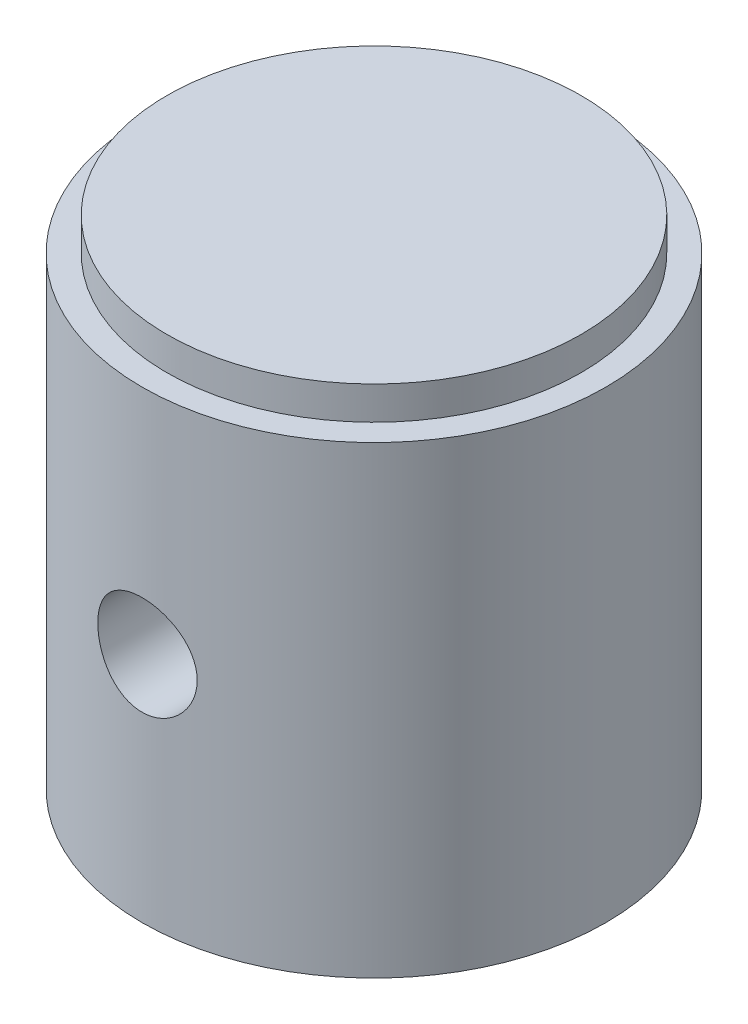
SolidWorks part; units mm, degrees
material "1023 Carbon Steel Sheet (SS)"
ref_plane "Front Plane" through (0, 0, 0) normal (0, 0, 1) x (1, 0, 0)
ref_plane "Top Plane" through (0, 0, 0) normal (0, 1, 0) x (1, 0, 0)
ref_plane "Right Plane" through (0, 0, 0) normal (1, 0, 0) x (0, 0, -1)
sketch "Sketch1" plane through (0, 0, 0) normal (0, 0, 1) x (1, 0, 0)
  line L0 (0, -1.1459) -> (0, 1.1459) construction
  line L1 (0, 1.1459) -> (-6.25, 1.1459)
  line L2 (-6.25, 1.1459) -> (-6.25, 0.1459)
  line L3 (-6.25, 0.1459) -> (-7, 0.1459)
  line L4 (-7, 0.1459) -> (-7, -13.8541)
  line L5 (-7, -13.8541) -> (-6.25, -13.8541)
  line L8 (-4.75, -2.8541) -> (0, 0)
  line L9 (0, 0) -> (0, 1.1459)
  line L10 (-6.25, -13.8541) -> (-4.75, -9.7329)
  line L11 (-4.75, -9.7329) -> (-4.75, -2.8541)
  point P4 (0, 0)
  dimension "D1" = 6.25
  dimension "D2" = 7
  dimension "D3" = 15
  dimension "D4" = 1
  dimension "D5" = 6.25
  dimension "D6" = 4.75
  dimension "D7" = 20
  dimension "D8" = 59
  dimension "D9" = 11
revolve "Revolve1" add sketch "Sketch1" angle 360 about L0
sketch "Sketch2" plane through (0, 0, 0) normal (0, 0, 1) x (1, 0, 0)
  line L0 (-7, -13.8541) -> (7, -13.8541) construction
  circle A0 centre (0, -6.8541) radius 1.5
  dimension "D1" = 3
  dimension "D2" = 7
extrude "Cut-Extrude1" cut sketch "Sketch2" against normal through all both and the other way through all
